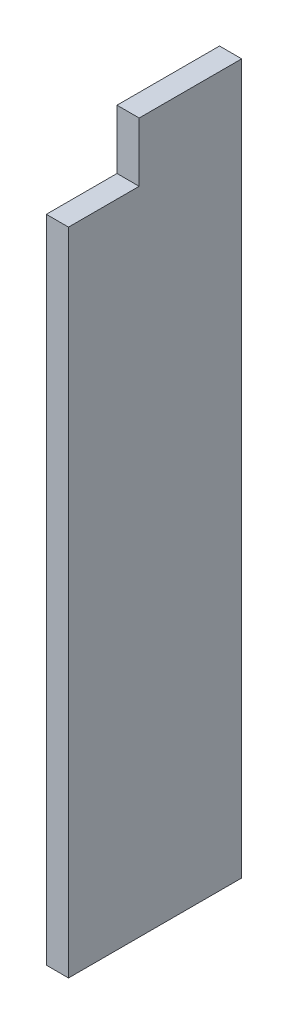
SolidWorks part; units mm, degrees
ref_plane "Alzado" through (0, 0, 0) normal (0, 0, 1) x (1, 0, 0)
ref_plane "Planta" through (0, 0, 0) normal (0, 1, 0) x (1, 0, 0)
ref_plane "Vista lateral" through (0, 0, 0) normal (1, 0, 0) x (0, 0, -1)
sketch "Croquis1" plane through (0, 0, 0) normal (1, 0, 0) x (0, 0, -1)
  line L0 (32.9793, 692.185) -> (32.9793, 779.4142)
  line L1 (32.9793, 779.4142) -> (-87.1554, 779.4142)
  line L2 (-169.966, 710.0856) -> (-169.966, -52.0111)
  line L3 (-169.966, -52.0111) -> (32.9793, -52.0111)
  line L4 (32.9793, 692.185) -> (32.9793, -52.0111)
  line L5 (-169.966, 710.0856) -> (32.9793, -52.0111) construction
  line L6 (-169.966, -52.0111) -> (32.9793, 692.185) construction
  line L7 (-87.1554, 779.4142) -> (-87.1554, 710.0856)
  line L8 (-87.1554, 710.0856) -> (-169.966, 710.0856)
  point P0 (-67.2875, 324.5089)
extrude "Saliente-Extruir1" add sketch "Croquis1" along normal blind 26
